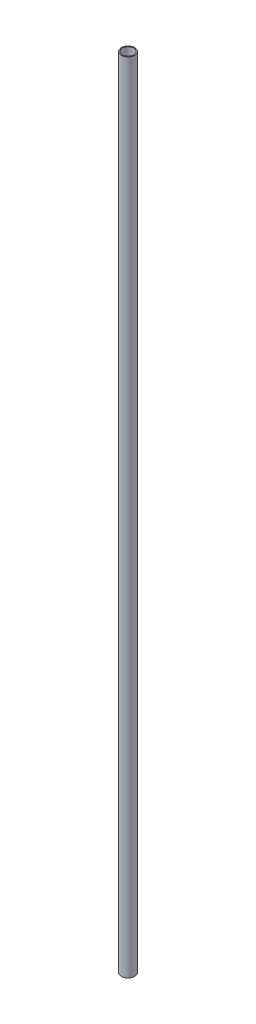
SolidWorks part; units mm, degrees
material "AISI Type 316L stainless steel"
ref_plane "Front Plane" through (0, 0, 0) normal (0, 0, 1) x (1, 0, 0)
ref_plane "Top Plane" through (0, 0, 0) normal (0, 1, 0) x (1, 0, 0)
ref_plane "Right Plane" through (0, 0, 0) normal (1, 0, 0) x (0, 0, -1)
sketch "Sketch1" plane through (0, 0, 0) normal (0, 1, 0) x (1, 0, 0)
  circle A0 centre (0, 0) radius 6.5
  circle A1 centre (0, 0) radius 7.5
  dimension "D1" = 15
  dimension "D2" = 1
extrude "Boss-Extrude1" add sketch "Sketch1" against normal blind 890 contours A1
